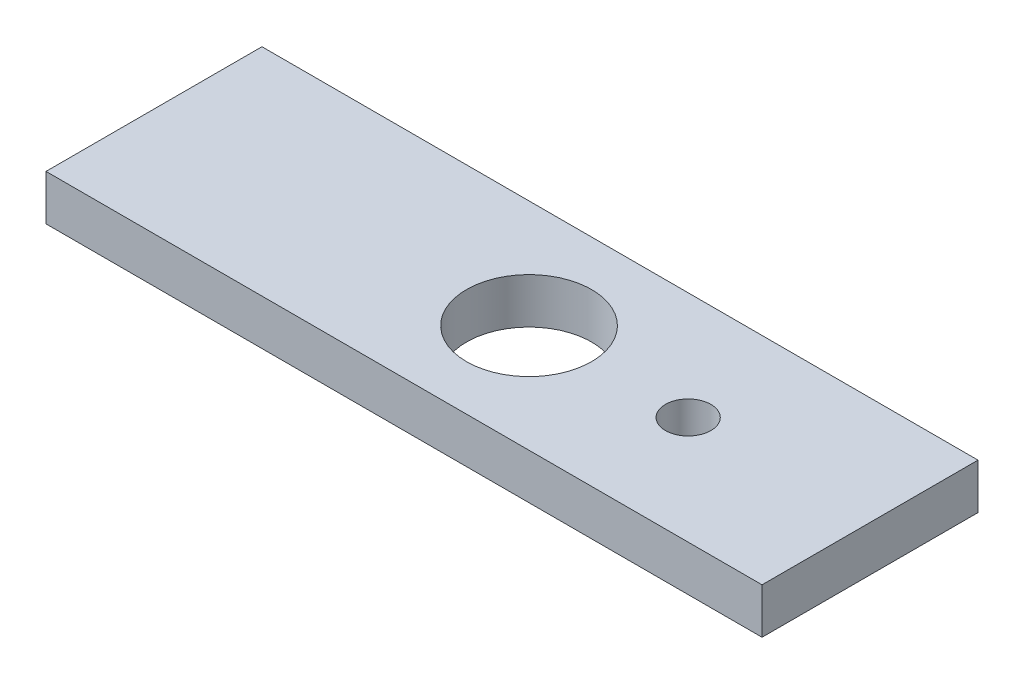
SolidWorks part; units mm, degrees
ref_plane "Front Plane" through (0, 0, 0) normal (0, 0, 1) x (1, 0, 0)
ref_plane "Top Plane" through (0, 0, 0) normal (0, 1, 0) x (1, 0, 0)
ref_plane "Right Plane" through (0, 0, 0) normal (1, 0, 0) x (0, 0, -1)
sketch "Sketch1" plane through (0, 0, 0) normal (0, 1, 0) x (1, 0, 0)
  line L1 (-31.5, -9.5) -> (31.5, -9.5)
  line L2 (-31.5, -9.5) -> (-31.5, 9.5)
  line L3 (-31.5, 9.5) -> (31.5, 9.5)
  line L4 (31.5, -9.5) -> (31.5, 9.5)
  line L5 (-31.5, -9.5) -> (31.5, 9.5) construction
  line L6 (-31.5, 9.5) -> (31.5, -9.5) construction
  point P0 (0, 0)
  dimension "D1" = 19
  dimension "D2" = 63
extrude "Boss-Extrude1" add sketch "Sketch1" along normal blind 4
sketch "Sketch2" plane through (0, 4, 0) normal (0, 1, 0) x (1, 0, 0)
  circle A0 centre (1.5, 0) radius 5.5
  circle A1 centre (15.5, 0) radius 2
extrude "Cut-Extrude1" cut sketch "Sketch2" against normal through all
